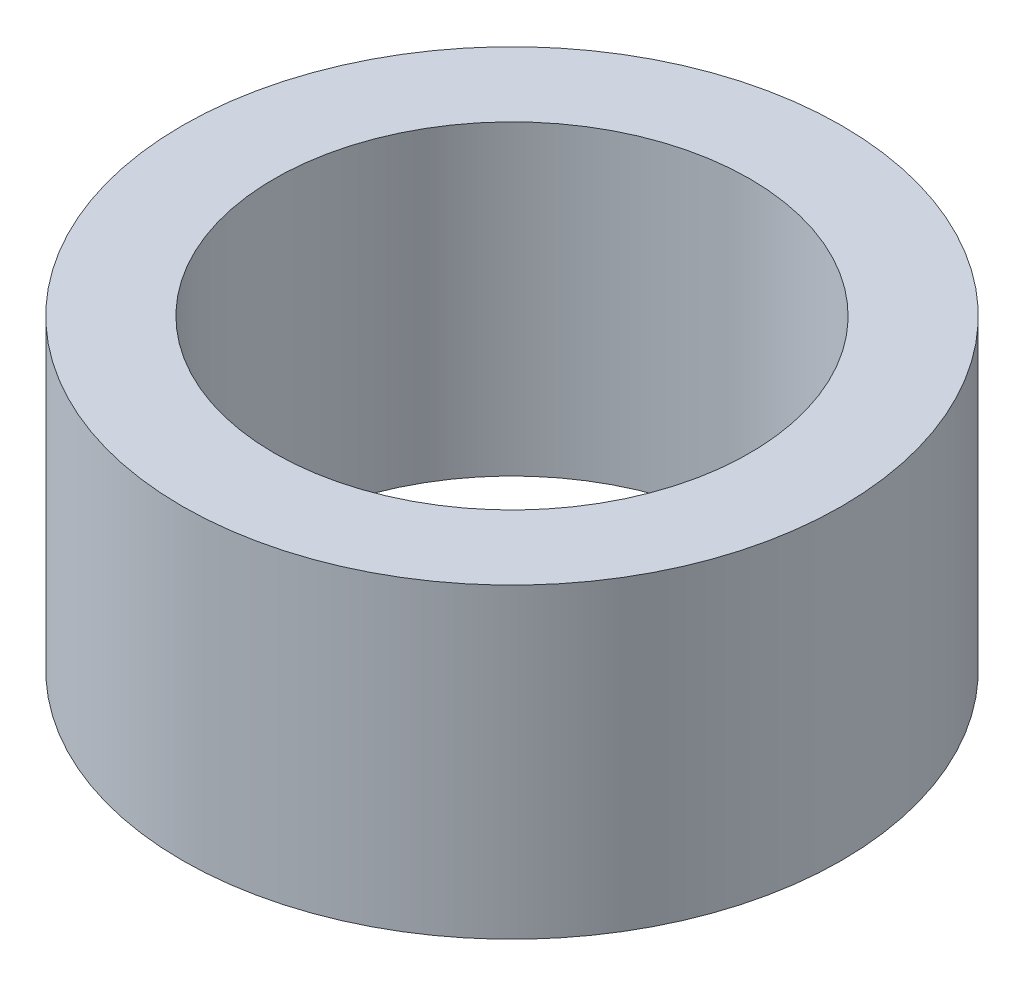
SolidWorks part; units mm, degrees
material "橡胶"
ref_plane "前视基准面" through (0, 0, 0) normal (0, 0, 1) x (1, 0, 0)
ref_plane "上视基准面" through (0, 0, 0) normal (0, 1, 0) x (1, 0, 0)
ref_plane "右视基准面" through (0, 0, 0) normal (1, 0, 0) x (0, 0, -1)
other "Configuration Table"
sketch "草图1" plane through (0, 0, 0) normal (0, 1, 0) x (1, 0, 0)
  circle A0 centre (0, 0) radius 15.5
  circle A1 centre (0, 0) radius 21.5
  dimension "D1" = 43
  dimension "D2" = 31
extrude "凸台-拉伸1" add sketch "草图1" along normal blind 20
